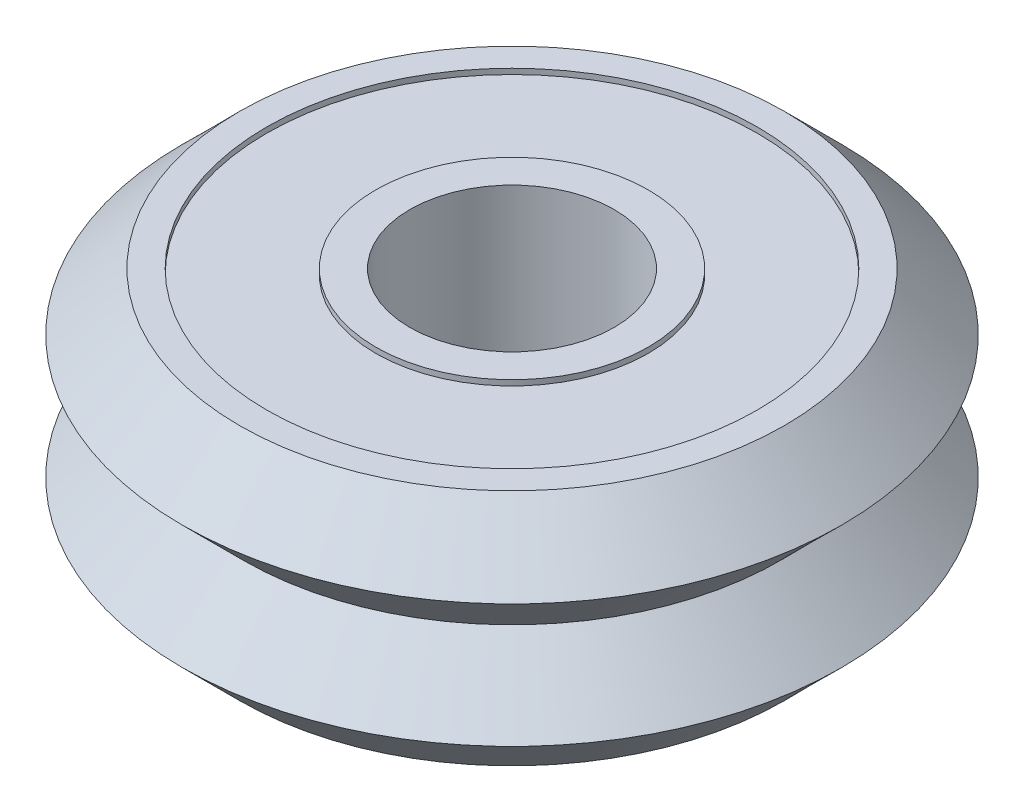
SolidWorks part; units mm, degrees
material "Plain Carbon Steel"
ref_plane "Front Plane" through (0, 0, 0) normal (0, 0, 1) x (1, 0, 0)
ref_plane "Top Plane" through (0, 0, 0) normal (0, 1, 0) x (1, 0, 0)
ref_plane "Right Plane" through (0, 0, 0) normal (1, 0, 0) x (0, 0, -1)
ref_plane "Plane1" through (0, 0, 0) normal (0, 0, -1) x (-1, 0, 0)
sketch "Sketch1" plane through (0, 0, 0) normal (0, 0, -1) x (-1, 0, 0)
  line L0 (-11.43, 5.296) -> (-11.43, 5.55)
  line L1 (-11.43, 5.55) -> (-12.69, 5.55)
  line L2 (-12.69, 5.55) -> (-15.365, 2.875)
  line L3 (-15.365, 2.875) -> (-12.49, 0)
  line L4 (-12.49, 0) -> (-15.365, -2.875)
  line L5 (-15.365, -2.875) -> (-12.69, -5.55)
  line L6 (-12.69, -5.55) -> (-11.43, -5.55)
  line L7 (-11.43, -5.55) -> (-11.43, -5.296)
  line L8 (-11.43, -5.296) -> (-6.35, -5.296)
  line L9 (-6.35, -5.296) -> (-6.35, -5.55)
  line L10 (-6.35, -5.55) -> (-4.7625, -5.55)
  line L11 (-4.7625, -5.55) -> (-4.7625, 5.55)
  line L12 (-4.7625, 5.55) -> (-6.35, 5.55)
  line L13 (-6.35, 5.55) -> (-6.35, 5.296)
  line L14 (-6.35, 5.296) -> (-11.43, 5.296)
  line L15 (0, -5.55) -> (0, 5.55) construction
revolve "Revolve1" add sketch "Sketch1" angle 360 about L15
